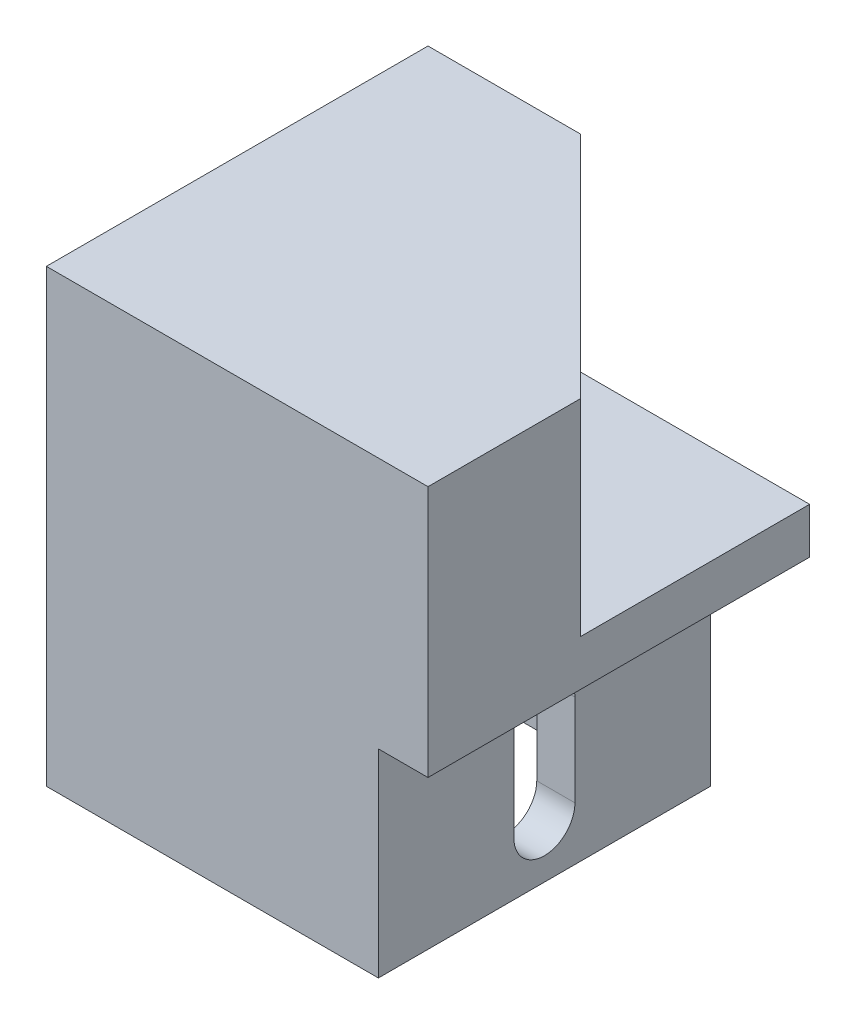
SolidWorks part; units mm, degrees
ref_plane "Alzado" through (0, 0, 0) normal (0, 0, 1) x (1, 0, 0)
ref_plane "Planta" through (0, 0, 0) normal (0, 1, 0) x (1, 0, 0)
ref_plane "Vista lateral" through (0, 0, 0) normal (1, 0, 0) x (0, 0, -1)
sketch "Croquis1" plane through (0, 0, 0) normal (0, 1, 0) x (1, 0, 0)
  line L0 (0, 0) -> (15, 0)
  line L1 (15, 0) -> (15, -10)
  line L2 (15, -10) -> (-10, -10)
  line L3 (-10, -10) -> (-10, 15)
  line L4 (-10, 15) -> (0, 15)
  line L5 (0, 15) -> (0, 0)
  dimension "D1" = 25
  dimension "D2" = 25
  dimension "D3" = 10
  dimension "D4" = 10
extrude "Saliente-Extruir1" add sketch "Croquis1" along normal mid plane 11.5
sketch "Croquis2" plane through (0, -5.75, 0) normal (0, -1, 0) x (1, 0, 0)
  line L1 (-10, 10) -> (15, 10)
  line L2 (-10, 10) -> (-10, -15)
  line L3 (-10, -15) -> (15, -15)
  line L4 (15, 10) -> (15, -15)
extrude "Saliente-Extruir2" add sketch "Croquis2" along normal blind 3
sketch "Croquis3" plane through (0, -8.75, 0) normal (0, -1, 0) x (1, 0, 0)
  line L0 (2.5, 10) -> (2.5, -15) construction
  line L1 (15, 10) -> (-10, 10) construction
  line L2 (-10, -15) -> (15, -15) construction
  line L4 (-4.25, -9.25) -> (9.25, -9.25)
  line L5 (-4.25, -9.25) -> (-4.25, 4.25)
  line L6 (-4.25, 4.25) -> (9.25, 4.25)
  line L7 (9.25, -9.25) -> (9.25, 4.25)
  line L8 (-4.25, -9.25) -> (9.25, 4.25) construction
  line L9 (-4.25, 4.25) -> (9.25, -9.25) construction
  line L14 (-10, 10) -> (11.75, 10)
  line L15 (-10, 10) -> (-10, -11.75)
  line L16 (-10, -11.75) -> (11.75, -11.75)
  line L17 (11.75, 10) -> (11.75, -11.75)
  point P6 (2.5, -2.5)
  dimension "D1" = 13.5
  dimension "D2" = 13.5
  dimension "D3" = 2.5
  dimension "D4" = 2.5
extrude "Saliente-Extruir3" add sketch "Croquis3" along normal blind 13
sketch "Croquis4" plane through (11.75, 0, 0) normal (1, 0, 0) x (0, 0, -1)
  line L0 (0.875, -12.25) -> (0.875, -18.25) construction
  line L1 (2.875, -12.25) -> (2.875, -18.25)
  line L2 (-1.125, -12.25) -> (-1.125, -18.25)
  line L3 (0.875, -8.75) -> (0.875, -21.75) construction
  line L4 (11.75, -8.75) -> (-10, -8.75)
  line L5 (-10, -8.75) -> (-10, -21.75)
  line L6 (-10, -21.75) -> (11.75, -21.75)
  line L7 (11.75, -21.75) -> (11.75, -8.75)
  line L8 (11.75, -8.75) -> (-10, -8.75)
  line L9 (-10, -8.75) -> (-10, -21.75)
  line L10 (-10, -21.75) -> (11.75, -21.75)
  line L11 (11.75, -21.75) -> (11.75, -8.75)
  line L12 (-10, -15.25) -> (11.75, -15.25) construction
  arc A0 (2.875, -12.25) -> (-1.125, -12.25) centre (0.875, -12.25) ccw
  arc A1 (-1.125, -18.25) -> (2.875, -18.25) centre (0.875, -18.25) ccw
  point P6 (0.875, -15.25)
  dimension "D2" = 4
  dimension "D3" = 6
  dimension "D1" = 0
extrude "Cortar-Extruir1" cut sketch "Croquis4" against normal blind 13 contours L2 A1 L1 A0
sketch "Croquis6" plane through (0, 0, -11.75) normal (0, 0, -1) x (-1, 0, 0)
  line L0 (-0.875, -12.25) -> (-0.875, -18.25) construction
  line L1 (1.125, -12.25) -> (1.125, -18.25)
  line L2 (-2.875, -12.25) -> (-2.875, -18.25)
  line L3 (-0.875, -8.75) -> (-0.875, -21.75) construction
  line L4 (10, -21.75) -> (10, -8.75) construction
  line L5 (10, -8.75) -> (-15, -8.75) construction
  line L6 (-11.75, -21.75) -> (-11.75, -8.75) construction
  line L8 (10, -8.75) -> (-11.75, -8.75)
  line L9 (-11.75, -8.75) -> (-11.75, -21.75)
  line L10 (-11.75, -21.75) -> (10, -21.75)
  line L11 (10, -21.75) -> (10, -8.75)
  line L12 (-11.75, -15.25) -> (10, -15.25) construction
  arc A0 (1.125, -12.25) -> (-2.875, -12.25) centre (-0.875, -12.25) ccw
  arc A1 (-2.875, -18.25) -> (1.125, -18.25) centre (-0.875, -18.25) ccw
  point P6 (-0.875, -15.25)
  point P19 (10, -15.25)
  dimension "D2" = 4
  dimension "D3" = 6
extrude "Cortar-Extruir2" cut sketch "Croquis6" against normal blind 13 contours L2 A1 L1 A0
sketch "Croquis7" plane through (0, 5.75, 0) normal (0, 1, 0) x (1, 0, 0)
  line L0 (15, 0) -> (0, 15)
  line L1 (0, 0) -> (15, 0)
  line L6 (0, 0) -> (0, 15)
  line L7 (0, 15) -> (-10, 15)
  line L8 (-10, 15) -> (-10, -10)
  line L9 (-10, -10) -> (15, -10)
  line L10 (15, -10) -> (15, 0)
  line L11 (15, 0) -> (0, 0)
  line L12 (0, 0) -> (0, 15)
  line L13 (0, 15) -> (-10, 15)
  line L14 (-10, 15) -> (-10, -10)
  line L15 (-10, -10) -> (15, -10)
  line L16 (15, -10) -> (15, 0)
  line L17 (15, 0) -> (0, 0)
  line M7 (0, 0) -> (0, 15)
  line M8 (0, 15) -> (-10, 15)
  line M9 (-10, 15) -> (-10, -10)
  line M10 (-10, -10) -> (15, -10)
  line M11 (15, -10) -> (15, 0)
  line M12 (15, 0) -> (0, 0)
  dimension "D1" = 0
extrude "Saliente-Extruir4" add sketch "Croquis7" along normal blind 2 contours L0 M12 M7 | M12 M7 M8 M9 M10 M11
